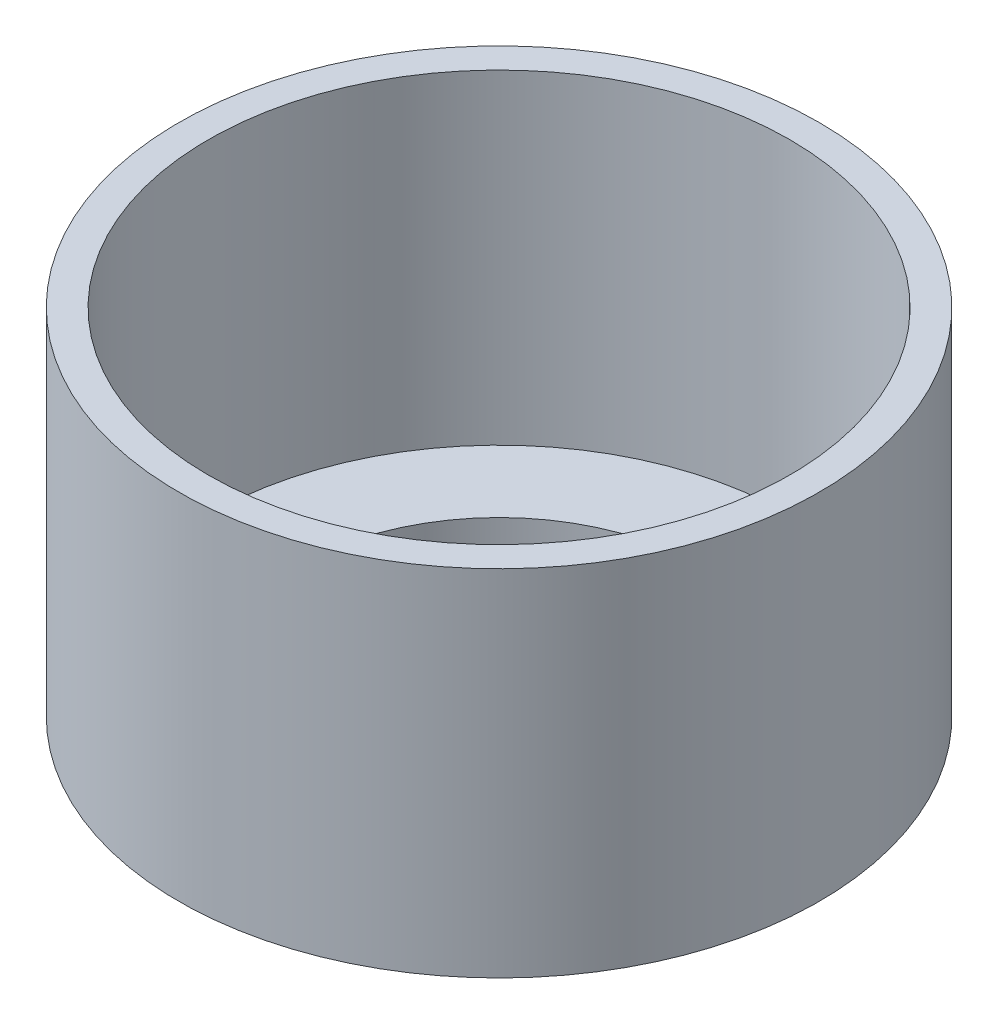
SolidWorks part; units mm, degrees
ref_plane "Front Plane" through (0, 0, 0) normal (0, 0, 1) x (1, 0, 0)
ref_plane "Top Plane" through (0, 0, 0) normal (0, 1, 0) x (1, 0, 0)
ref_plane "Right Plane" through (0, 0, 0) normal (1, 0, 0) x (0, 0, -1)
sketch "Sketch1" plane through (0, 0, 0) normal (0, 1, 0) x (1, 0, 0)
  circle A0 centre (0, 0) radius 68.842
extrude "Boss-Extrude1" add sketch "Sketch1" along normal blind 76.2
sketch "Sketch2" plane through (0, 76.2, 0) normal (0, 1, 0) x (1, 0, 0)
  circle A2 centre (0, 0) radius 62.492
  circle A3 centre (0, 0) radius 62.492
  dimension "D1" = 6.35
extrude "Cut-Extrude1" cut sketch "Sketch2" against normal offset from surface (69.85 mm away) 6.35 up to face at (0, 0, 68.842)
sketch "Sketch3" plane through (0, 6.35, 0) normal (0, 1, 0) x (1, 0, 0)
  circle A2 centre (0, 0) radius 43.442
  circle A3 centre (0, 0) radius 43.442
  dimension "D1" = 19.05
extrude "Cut-Extrude2" cut sketch "Sketch3" against normal through all
